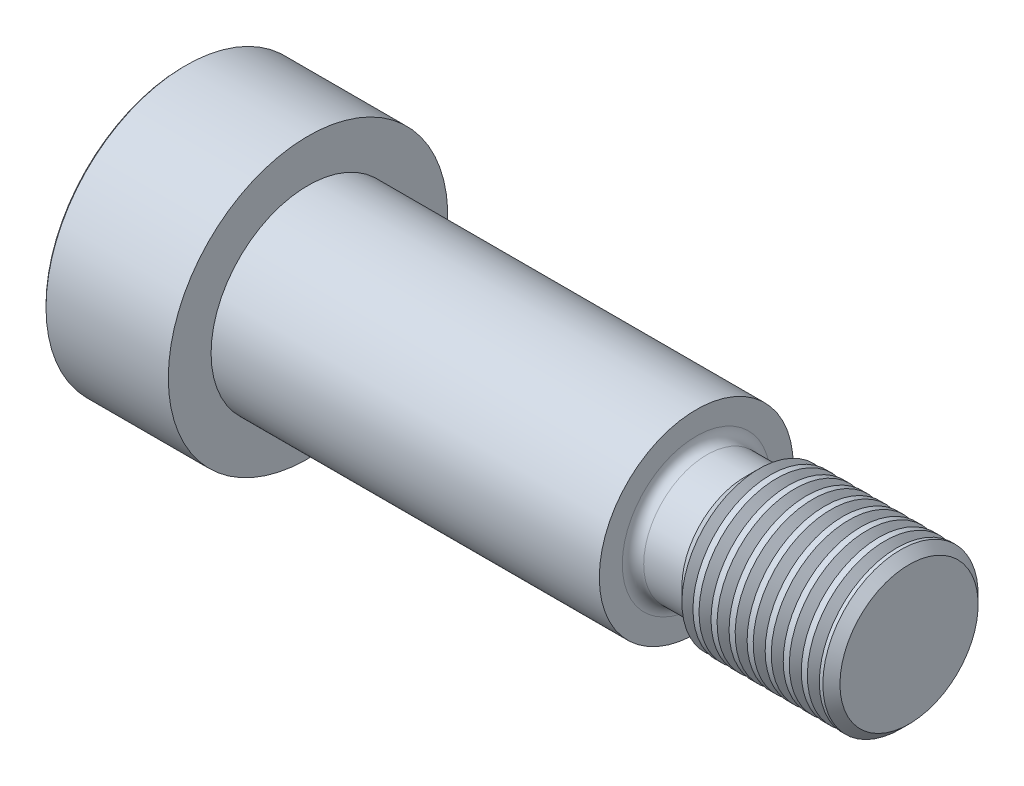
SolidWorks part; units mm, degrees
ref_plane "Plane1" through (0, 0, 0) normal (0, 0, 1) x (1, 0, 0)
ref_plane "Plane2" through (0, 0, 0) normal (0, 1, 0) x (1, 0, 0)
ref_plane "Plane3" through (0, 0, 0) normal (1, 0, 0) x (0, 0, -1)
sketch "BodySke" plane through (0, 0, 0) normal (0, 0, 1) x (1, 0, 0)
  line L0 (0, 0) -> (0, 18)
  line L2 (0, 18) -> (16, 18)
  line L3 (16, 18) -> (16, 12.49)
  line L6 (16, 12.49) -> (66, 12.49)
  line L7 (66, 12.49) -> (66, 9.53)
  line L8 (67.38, 8.15) -> (72.3, 8.15)
  line L9 (72.3, 8.15) -> (74.15, 10)
  line L10 (74.15, 10) -> (92.2985, 10)
  line L11 (92.2985, 10) -> (93.4, 8.8985)
  line L12 (93.4, 8.8985) -> (93.4, 0)
  line L13 (93.4, 0) -> (0, 0)
  line L14 (-6.35, 0) -> (107.95, 0) construction
  line L15 (92.2985, -10) -> (93.4, -8.8985) construction
  line L16 (66, -8.15) -> (72.3, -8.15) construction
  line L17 (16, -12.49) -> (66, -12.49) construction
  line L20 (74.8, 13.0014) -> (74.8, -4.3514) construction
  line L21 (70.54, 7.0856) -> (70.54, -8.764) construction
  arc A0 (66, 9.53) -> (67.38, 8.15) centre (67.38, 9.53) ccw
  point P29 (66, 8.15)
  dimension "Thread_neck_fillet_rad" = 1.38
  dimension "Head_dia" = 36
  dimension "Head_ht" = 16
  dimension "Diameter" = 24.98
  dimension "Thread_dia" = 20
  dimension "Minor_dia" = 17.797
  dimension "Thread_ch_ang" = 45
  dimension "Thread_neck_dia" = 16.3
  dimension "D11" = 45
  dimension "Thread_length" = 27.4
  dimension "Length" = 50
  dimension "Thread_neck_width" = 6.3
  dimension "Advance" = 2.5
  dimension "Thread_nom" = 22.86
  dimension "Thread_lim" = 18.6
revolve "BaseBody" add sketch "BodySke"
cosmetic thread "ThreadCosmetic" [suppressed]
pattern_linear "ThdSchPat" count 8 spacing 2.325 along (1, 0, 0)
revolve "ThreadSchematic" cut sketch "ThdSchSke" angle 360 about L3
sketch "ThdSchSke" plane through (0, 0, 0) normal (0, 0, 1) x (1, 0, 0)
  line L0 (74.8, -8.8985) -> (72.2852, -12.49)
  line L1 (74.8, -8.8985) -> (77.3148, -12.49)
  line L2 (77.3148, -12.49) -> (77.3148, -15.6125)
  line L3 (-3.175, 0) -> (5.1513, 0) construction
  line L5 (77.3148, -15.6125) -> (72.2852, -15.6125)
  line L6 (72.2852, -15.6125) -> (72.2852, -12.49)
  dimension "Thread_minor" = 17.797
  dimension "Diameter" = 24.98
  dimension "Start" = 74.8
  dimension "SideAngle" = 55
  dimension "VeeAngle" = 70
  dimension "Overcut" = 31.225
chamfer "Chamfer1" distance 0.25 1 edges at (0, 0, 18)
sketch "Sketch2" plane through (0, 0, 0) normal (0, 0, 1) x (1, 0, 0)
  line L0 (0, 6) -> (10, 6)
  line L1 (10, 6) -> (13.4641, 0)
  line L3 (13.4641, 0) -> (0, 0)
  line L4 (0, 0) -> (0, 6)
  line L5 (0, -6) -> (10, -6) construction
  line L6 (0, 0) -> (47.625, 0) construction
  dimension "D2" = 60
  dimension "PreBroach_depth" = 10
  dimension "PreBroach_dia" = 12
revolve "PreBroach" cut sketch "Sketch2" angle 360 about L6
sketch "Sketch3" plane through (0, 0, 0) normal (-1, 0, 0) x (0, 0, 1)
  line L0 (-6, -3.4641) -> (-6, 3.4641)
  line L1 (-6, 3.4641) -> (0, 6.9282)
  line L2 (0, 6.9282) -> (6, 3.4641)
  line L3 (6, 3.4641) -> (6, -3.4641)
  line L4 (6, -3.4641) -> (0, -6.9282)
  line L5 (0, -6.9282) -> (-6, -3.4641)
  dimension "D1" = 6
  dimension "Hex_size" = 12
  dimension "D2" = 6
  dimension "D3" = 120
  dimension "D4" = 12
extrude "Hex" cut sketch "Sketch3" against normal blind 10
equation "\"Thread_minor@ThreadCosmetic\" = \"Minor_dia@BodySke\""
equation "\"D1@Sketch3\" = \"Hex_size@Sketch3\" / 2"
equation "\"D2@Sketch3\" = \"D1@Sketch3\""
equation "\"D4@Sketch3\" = \"Hex_size@Sketch3\""
equation "\"Thread_length@ThreadCosmetic\" = ((sgn( (\"Thread_length@BodySke\" - \"Advance@BodySke\" - \"Thread_neck_width@BodySke\" ) - \"Thread_nom@BodySke\" )-1)*( (\"Thread_length@BodySke\" - \"Advance@BodySke\" - \"Thread_neck_width@BodySke\" ) - \"Thread_nom@BodySke\" ))/-2+ \"Thread_nom@BodySke\""
equation "\"Thread_minor@ThdSchSke\" = \"Minor_dia@BodySke\""
equation "\"Diameter@ThdSchSke\" = \"Diameter@BodySke\""
equation "\"Overcut@ThdSchSke\" = \"Diameter@BodySke\" * 1.25"
equation "\"Start@ThdSchSke\" = \"Head_ht@BodySke\" + \"Length@BodySke\" + \"Thread_length@BodySke\" -  \"Thread_length@ThreadCosmetic\"  '---Non-countersunk---"
equation "\"Num_threads@ThdSchPat\" = int( \"Thread_length@ThreadCosmetic\" / \"Advance@BodySke\" + 0.999 ) + 1"
equation "\"Advance@ThdSchPat\" = \"Thread_length@ThreadCosmetic\" /  (\"Num_threads@ThdSchPat\" - 1) 'relax it"
equation "\"Num_threads@ThdSchPat\" = \"Num_threads@ThdSchPat\" - sgn( \"Num_threads@ThdSchPat\" - 1) '---chamfered tips only---"
